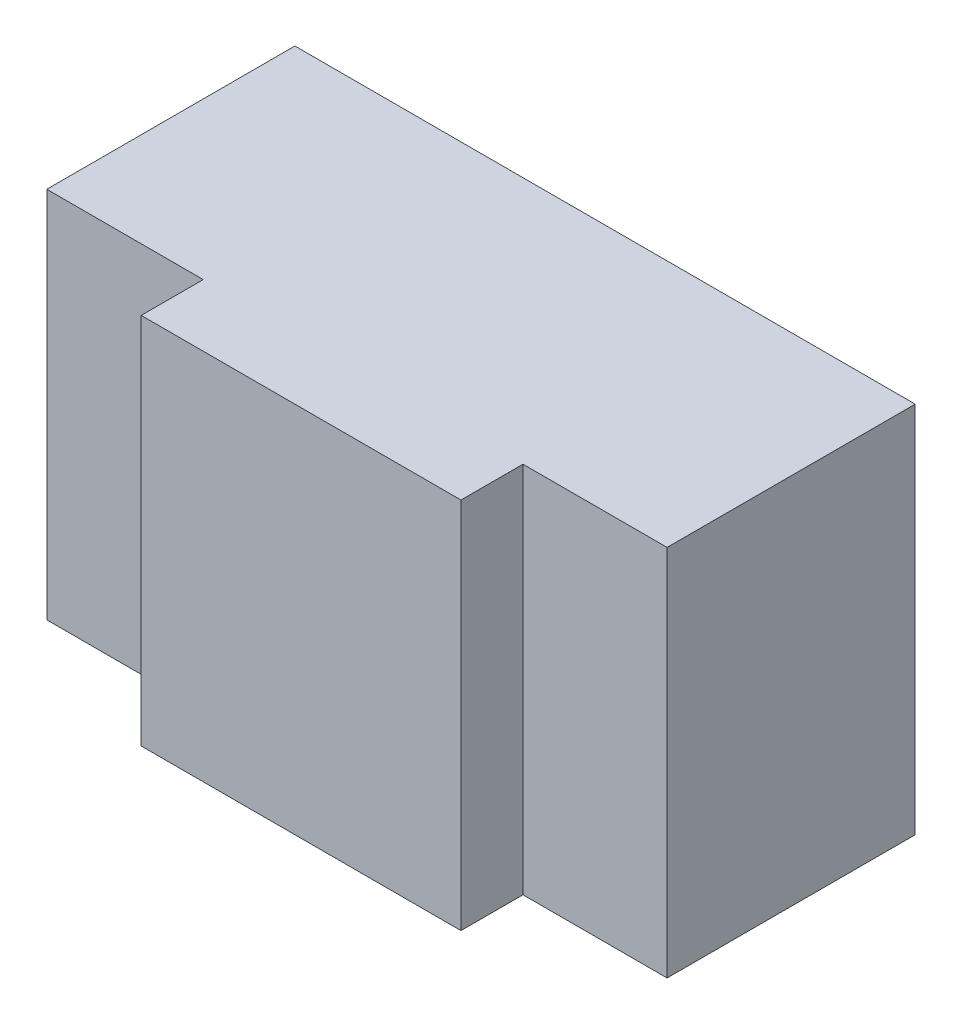
SolidWorks part; units mm, degrees
ref_plane "前视基准面" through (0, 0, 0) normal (0, 0, 1) x (1, 0, 0)
ref_plane "上视基准面" through (0, 0, 0) normal (0, 1, 0) x (1, 0, 0)
ref_plane "右视基准面" through (0, 0, 0) normal (1, 0, 0) x (0, 0, -1)
sketch "草图1" plane through (0, 0, 0) normal (0, 0, 1) x (1, 0, 0)
  line L1 (0, 0) -> (-1, 0)
  line L2 (0, 0) -> (0, 0.6012)
  line L3 (0, 0.6012) -> (-1, 0.6012)
  line L4 (-1, 0) -> (-1, 0.6012)
  dimension "D1" = 1
  dimension "D2" = 0.6012
extrude "凸台-拉伸1" add sketch "草图1" along normal blind 0.5
sketch "草图2" plane through (0, 0, 0.5) normal (0, 0, 1) x (1, 0, 0)
  line L0 (0, 0.6012) -> (-1, 0.6012) construction
  line L1 (-0.7478, 0.6012) -> (-0.2323, 0.6012)
  line L2 (-0.7478, 0.6012) -> (-0.7478, 0)
  line L3 (-0.7478, 0) -> (-0.2323, 0)
  line L4 (-0.2323, 0.6012) -> (-0.2323, 0)
  line L5 (-1, 0) -> (0, 0) construction
extrude "切除-拉伸1" cut sketch "草图2" against normal blind 0.1 flip side to cut
